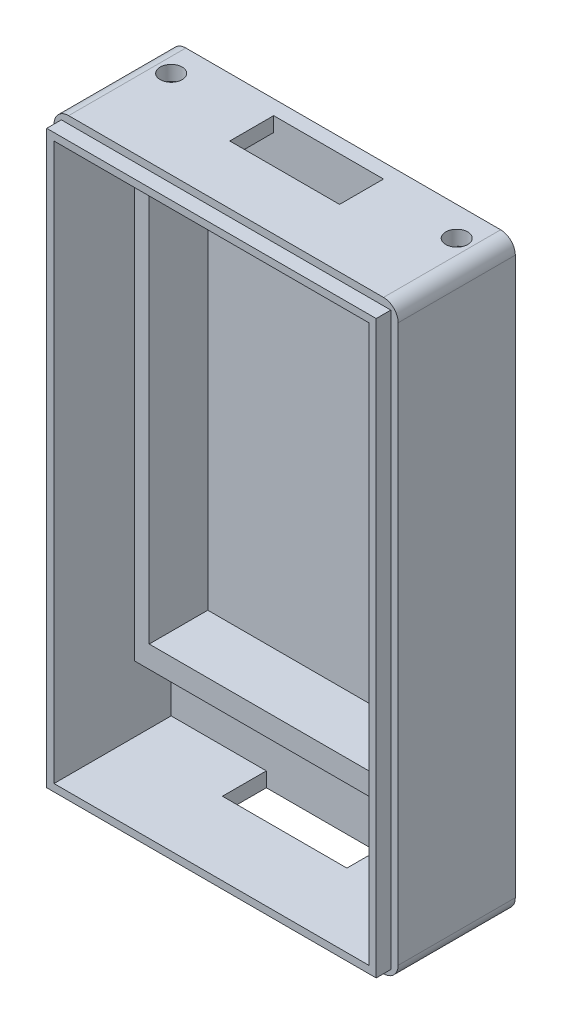
SolidWorks part; units mm, degrees
ref_plane "Front Plane" through (0, 0, 0) normal (0, 0, 1) x (1, 0, 0)
ref_plane "Top Plane" through (0, 0, 0) normal (0, 1, 0) x (1, 0, 0)
ref_plane "Right Plane" through (0, 0, 0) normal (1, 0, 0) x (0, 0, -1)
sketch "Sketch1" plane through (0, 0, 0) normal (0, 0, 1) x (1, 0, 0)
  line L1 (-23.5, 40) -> (23.5, 40)
  line L2 (-23.5, 40) -> (-23.5, -40)
  line L3 (-23.5, -40) -> (23.5, -40)
  line L4 (23.5, 40) -> (23.5, -40)
  line L5 (-23.5, 40) -> (23.5, -40) construction
  line L6 (-23.5, -40) -> (23.5, 40) construction
  point P0 (0, 0)
  dimension "D1" = 80
  dimension "D2" = 47
extrude "Boss-Extrude1" add sketch "Sketch1" along normal blind 18
sketch "Sketch2" plane through (0, 0, 18) normal (0, 0, 1) x (1, 0, 0)
  line L0 (-23.5, -40) -> (23.5, -40) construction
  line L1 (-21.5, 38) -> (21.5, 38)
  line L2 (-21.5, 38) -> (-21.5, -38)
  line L3 (-21.5, -38) -> (21.5, -38)
  line L4 (21.5, 38) -> (21.5, -38)
  line L5 (-21.5, 38) -> (21.5, -38) construction
  line L6 (-21.5, -38) -> (21.5, 38) construction
  line L9 (-23.5, 40) -> (-23.5, -40) construction
  point P0 (0, 0)
  dimension "D1" = 2
  dimension "D2" = 2
extrude "Cut-Extrude1" cut sketch "Sketch2" against normal blind 16
sketch "Sketch3" plane through (0, 0, 2) normal (0, 0, 1) x (1, 0, 0)
  line L1 (-18.5, 38) -> (-16.5, 38)
  line L2 (-18.5, 38) -> (-18.5, -26)
  line L4 (-16.5, 38) -> (-16.5, -23)
  line L5 (-21.5, 38) -> (-21.5, -38) construction
  line L7 (18.5, 38) -> (16.5, 38)
  line L8 (18.5, 38) -> (18.5, -26)
  line L10 (16.5, 38) -> (16.5, -23)
  line L11 (-18.5, -26) -> (18.5, -26)
  line L12 (-16.5, -23) -> (16.5, -23)
  line L13 (21.5, 38) -> (-21.5, 38) construction
  line L16 (21.5, -38) -> (21.5, 38) construction
  dimension "D1" = 3
  dimension "D2" = 2
  dimension "D3" = 3
  dimension "D4" = 2
  dimension "D5" = 3
  dimension "D6" = 64
extrude "Boss-Extrude2" add sketch "Sketch3" along normal blind 8
sketch "Sketch6" plane through (0, 38, 0) normal (0, -1, 0) x (1, 0, 0)
  line L0 (16.5, 2) -> (-16.5, 2) construction
  line L1 (-7.5, 2) -> (7.5, 2)
  line L2 (-7.5, 2) -> (-7.5, 8)
  line L3 (-7.5, 8) -> (7.5, 8)
  line L4 (7.5, 2) -> (7.5, 8)
  line L5 (-23.5, 18) -> (-23.5, 0) construction
  line L6 (23.5, 18) -> (23.5, 0) construction
  dimension "D1" = 6
  dimension "D2" = 16
  dimension "D3" = 16
extrude "Cut-Extrude4" cut sketch "Sketch6" against normal blind 11
sketch "Sketch8" plane through (0, 0, 18) normal (0, 0, 1) x (1, 0, 0)
  line L0 (-22.5, 39) -> (-22.5, -39)
  line L2 (-23.5, -40) -> (23.5, -40) construction
  line L4 (-23.5, -40) -> (-23.5, 40)
  line L6 (-23.5, 40) -> (23.5, 40)
  line L8 (22.5, 39) -> (-22.5, 39)
  line L10 (22.5, 39) -> (22.5, -39)
  line L12 (23.5, -40) -> (23.5, 40)
  line L13 (-23.5, -40) -> (23.5, -40)
  line L14 (22.5, -39) -> (-22.5, -39)
  dimension "D1" = 1
  dimension "D2" = 1
  dimension "D3" = 1
  dimension "D4" = 1
extrude "Cut-Extrude5" cut sketch "Sketch8" against normal blind 2
sketch "Sketch9" plane through (0, 40, 0) normal (0, 1, 0) x (1, 0, 0)
  line L0 (23.5, 0) -> (-23.5, 0) construction
  line L1 (-23.5, -16) -> (-23.5, 0) construction
  line L3 (0, -9.9) -> (0, 9.9) construction
  circle A0 centre (-19.5, -4) radius 1.5
  circle A3 centre (19.5, -4) radius 1.5
  dimension "D1" = 3
  dimension "D3" = 4
  dimension "D4" = 4
extrude "Cut-Extrude6" cut sketch "Sketch9" against normal blind 10
sketch "Sketch11" plane through (0, -38, 0) normal (0, 1, 0) x (1, 0, 0)
  line L0 (-21.5, -2) -> (21.5, -2) construction
  line L1 (-8.5, -2) -> (8.5, -2)
  line L2 (-8.5, -2) -> (-8.5, -8)
  line L3 (-8.5, -8) -> (8.5, -8)
  line L4 (8.5, -2) -> (8.5, -8)
  dimension "D1" = 15
  dimension "D2" = 15
  dimension "D3" = 6
extrude "Cut-Extrude9" cut sketch "Sketch11" against normal blind 10
fillet "Fillet4" radius 2 4 edges at (23.5, -40, 8) (-23.5, -40, 8) (-23.5, 40, 8) (23.5, 40, 8)
